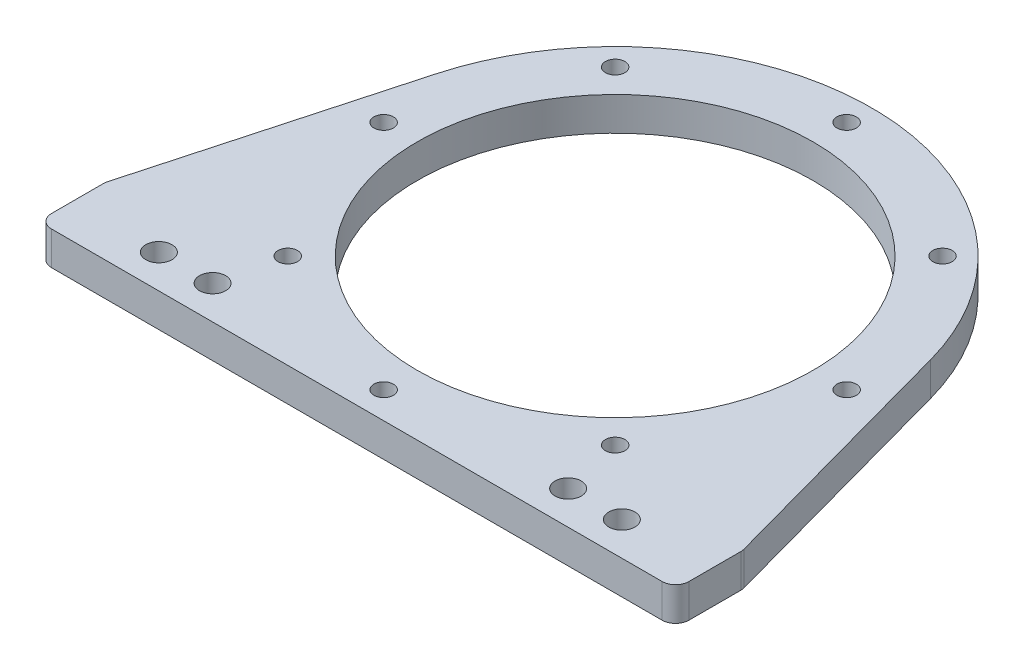
SolidWorks part; units mm, degrees
material "Thornel Mat VMA"
ref_plane "前视基准面" through (0, 0, 0) normal (0, 0, 1) x (1, 0, 0)
ref_plane "上视基准面" through (0, 0, 0) normal (0, 1, 0) x (1, 0, 0)
ref_plane "右视基准面" through (0, 0, 0) normal (1, 0, 0) x (0, 0, -1)
other "Configuration Table"
sketch "草图1" plane through (0, 0, 0) normal (0, 1, 0) x (1, 0, 0)
  line L0 (-36.8827, 10.1356) -> (-47.5, -28.5)
  line L1 (-47.5, -28.5) -> (-47.5, -38.5)
  line L2 (-47.5, -38.5) -> (47.5, -38.5)
  line L3 (47.5, -38.5) -> (47.5, -28.5)
  line L4 (47.5, -28.5) -> (36.8827, 10.1356)
  circle A0 centre (0, 0) radius 34.5 construction
  arc A1 (36.8827, 10.1356) -> (-36.8827, 10.1356) centre (0, 0) ccw
  circle A2 centre (0, 0) radius 29.5
  circle A3 centre (-34.5, 0) radius 1.45
  circle A4 centre (-24.3952, 24.3952) radius 1.45
  circle A5 centre (0, 34.5) radius 1.45
  circle A6 centre (24.3952, 24.3952) radius 1.45
  circle A7 centre (34.5, 0) radius 1.45
  circle A8 centre (24.3952, -24.3952) radius 1.45
  circle A9 centre (0, -34.5) radius 1.45
  circle A10 centre (-24.3952, -24.3952) radius 1.45
  dimension "D1" = 69
  dimension "D2" = 76.5
  dimension "D3" = 3.75
  dimension "D4" = 5
  dimension "D5" = 2.9
  dimension "D6" = 10
  dimension "D7" = 38.5
  dimension "D8" = 95
extrude "凸台-拉伸1" add sketch "草图1" along normal blind 5
sketch "草图2" plane through (0, 5, 0) normal (0, 1, 0) x (1, 0, 0)
  line L0 (-47.5, -33.5) -> (47.5, -33.5) construction
  line L1 (-47.5, -28.5) -> (-47.5, -38.5) construction
  line L2 (47.5, -38.5) -> (47.5, -28.5) construction
  circle A0 centre (-34.5, -33.5) radius 1.95
  circle A1 centre (-26.5, -33.5) radius 1.95
  circle A2 centre (26.5, -33.5) radius 1.95
  circle A3 centre (34.5, -33.5) radius 1.95
  dimension "D1" = 8
  dimension "D2" = 8
  dimension "D3" = 3.9
  dimension "D4" = 13
  dimension "D5" = 13
extrude "切除-拉伸1" cut sketch "草图2" against normal through all
fillet "圆角1" radius 2 4 edges at (47.5, 2.5, 28.5) (47.5, 2.5, 38.5) (-47.5, 2.5, 38.5) (-47.5, 2.5, 28.5)
